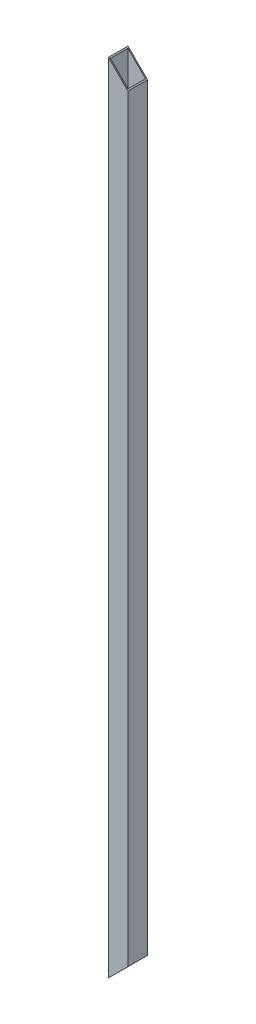
SolidWorks part; units mm, degrees
ref_plane "Front Plane" through (0, 0, 0) normal (0, 0, 1) x (1, 0, 0)
ref_plane "Top Plane" through (0, 0, 0) normal (0, 1, 0) x (1, 0, 0)
ref_plane "Right Plane" through (0, 0, 0) normal (1, 0, 0) x (0, 0, -1)
sketch "Sketch2" plane through (0, 1631.5, 0) normal (0, 1, 0) x (1, 0, 0)
  line L1 (925, 0) -> (965, 0)
  line L2 (925, 0) -> (925, 40)
  line L3 (925, 40) -> (965, 40)
  line L4 (965, 0) -> (965, 40)
  line L5 (927, 2) -> (963, 2)
  line L6 (963, 2) -> (963, 38)
  line L7 (927, 38) -> (963, 38)
  line L8 (927, 2) -> (927, 38)
  dimension "D1" = 40
  dimension "D3" = 40
  dimension "D4" = 2
extrude "Boss-Extrude1" add sketch "Sketch2" against normal up to surface (1631.5 mm away)
sketch "Sketch3" plane through (0, 0, 0) normal (0, 0, 1) x (1, 0, 0)
  line L0 (925, 1631.5) -> (965, 1591.5)
  line L1 (965, 0) -> (965, 1631.5) construction
  line L2 (965, 1591.5) -> (965, 1631.5)
  line L3 (965, 1631.5) -> (925, 1631.5)
  line L4 (925, 1631.5) -> (965, 1631.5)
  line L5 (925, 815.75) -> (965, 815.75) construction
  line L6 (925, 0) -> (925, 1631.5) construction
  line L7 (925, 0) -> (965, 0)
  line L8 (965, 0) -> (925, 0)
  line L9 (965, 40) -> (965, 0)
  line L10 (925, 0) -> (965, 40)
  line M5 (925, 0) -> (965, 0)
  line M6 (965, 0) -> (965, 1631.5)
  line M7 (965, 1631.5) -> (925, 1631.5)
  dimension "D1" = 45
extrude "Cut-Extrude1" cut sketch "Sketch3" against normal up to surface (40 mm away) contours L10 M5 M6 | L0 M7 M6 up to face at (945, 815.75, -40)
